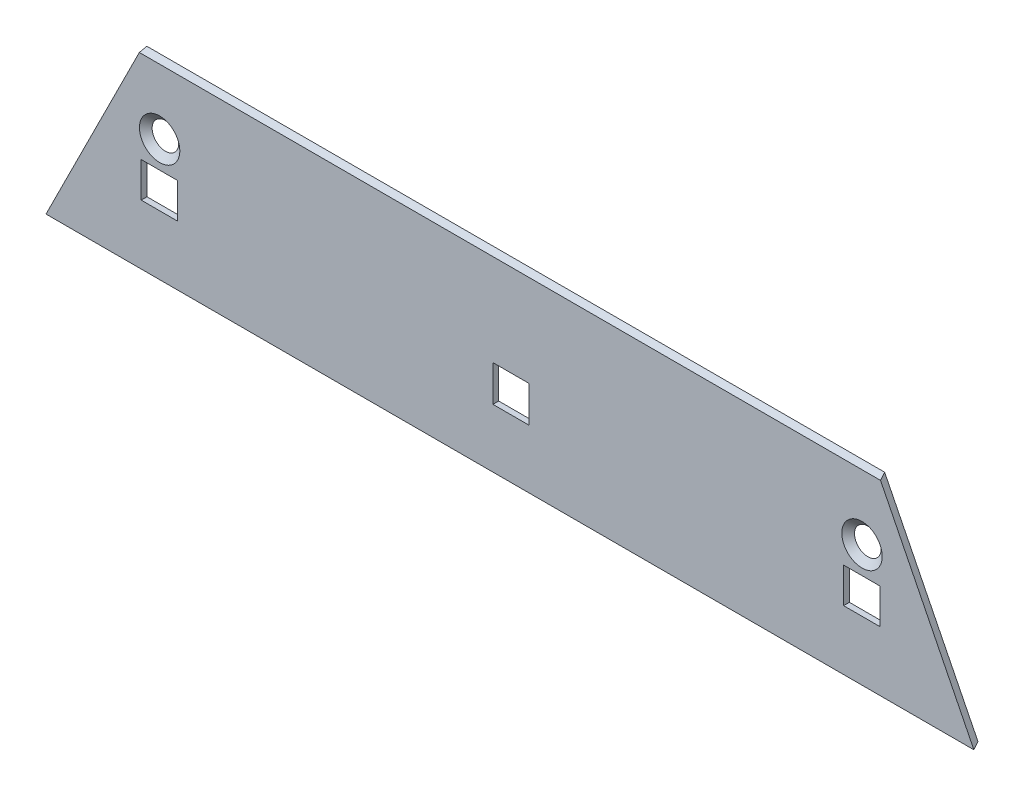
SolidWorks part; units mm, degrees
material "1023 Carbon Steel Sheet (SS)"
ref_plane "Front Plane" through (0, 0, 0) normal (0, 0, 1) x (1, 0, 0)
ref_plane "Top Plane" through (0, 0, 0) normal (0, 1, 0) x (1, 0, 0)
ref_plane "Right Plane" through (0, 0, 0) normal (1, 0, 0) x (0, 0, -1)
sketch "Sketch3" plane through (0, 0, 0) normal (1, 0, 0) x (0, 0, -1)
  line L0 (-0.5715, 31.42) -> (-1.5875, 30.8335)
  line L2 (-0.5715, -1.3309) -> (-0.5715, 31.42)
  line L3 (-1.5875, -1.9175) -> (-0.5715, -1.3309)
  line L4 (-1.5875, -1.9175) -> (-1.5875, 30.8335)
  dimension "D1" = 60
  dimension "D2" = 1.016
  dimension "D3" = 60
  dimension "D4" = 33.3375
extrude "Boss-Extrude2" add sketch "Sketch3" along normal blind 162.814
sketch "Sketch5" plane through (0, 0, 1.5875) normal (0, 0, 1) x (1, 0, 0)
  line L0 (0, -1.9175) -> (16.6723, 31.42)
  line L2 (16.6723, 31.42) -> (0, 31.42)
  line L3 (0, 31.42) -> (0, -1.9175)
  line L4 (162.814, -1.9175) -> (146.1417, 31.42)
  line L5 (146.1417, 31.42) -> (162.814, 31.42)
  line L6 (162.814, 31.42) -> (162.814, -1.9175)
  dimension "D1" = 26.57
  dimension "D2" = 26.57
extrude "Cut-Extrude1" cut sketch "Sketch5" against normal through all
sketch "Sketch6" plane through (0, 0, 1.5875) normal (0, 0, 1) x (1, 0, 0)
  line L1 (16.7056, 14.728) -> (23.0556, 14.728)
  line L2 (16.7056, 14.728) -> (16.7056, 8.5558)
  line L3 (16.7056, 8.5558) -> (23.0556, 8.5558)
  line L4 (23.0556, 14.728) -> (23.0556, 8.5558)
  line L5 (139.954, 14.728) -> (146.304, 14.728)
  line L6 (139.954, 14.728) -> (139.954, 8.5558)
  line L7 (139.954, 8.5558) -> (146.304, 8.5558)
  line L8 (146.304, 14.728) -> (146.304, 8.5558)
  line L9 (78.4187, 14.728) -> (84.7687, 14.728)
  line L10 (78.4187, 14.728) -> (78.4187, 8.378)
  line L11 (78.4187, 8.378) -> (84.7687, 8.378)
  line L12 (84.7687, 14.728) -> (84.7687, 8.378)
extrude "Cut-Extrude2" cut sketch "Sketch6" against normal through all
hole_wizard "CSK for #6 Flat Head Machine Screw (100)1" positions "Sketch8" profile "Sketch7" countersink size "#6" standard "ANSI Inch" end condition through all
sketch "Sketch8" plane through (0, 0, 1.5875) normal (0, 0, 1) x (1, 0, 0)
  point P0 (19.939, 19.427)
  point P3 (143.1874, 19.427)
  point P6 (143.1874, 19.427)
sketch "Sketch7" plane through (19.939, 19.427, 1.5875) normal (1, 0, 0) x (0, -1, 0)
  line L0 (0, 0) -> (0, 1.016)
  line L1 (0, 1.016) -> (1.8986, 1.016)
  line L2 (1.8986, 1.016) -> (1.8986, 1.38)
  line L3 (1.8986, 1.38) -> (3.5433, 0)
  line L5 (3.5433, 0) -> (0, 0)
  line L6 (-1.8987, 1.38) -> (-3.5433, 0) construction
  line L11 (0, -6.35) -> (0, 107.95) construction
  dimension "Thru Hole Dia." = 3.7973
  dimension "Thru Hole Depth" = 1.016
  dimension "Near C'Sink Dia." = 7.0866
  dimension "Near C'Sink Angle" = 100
